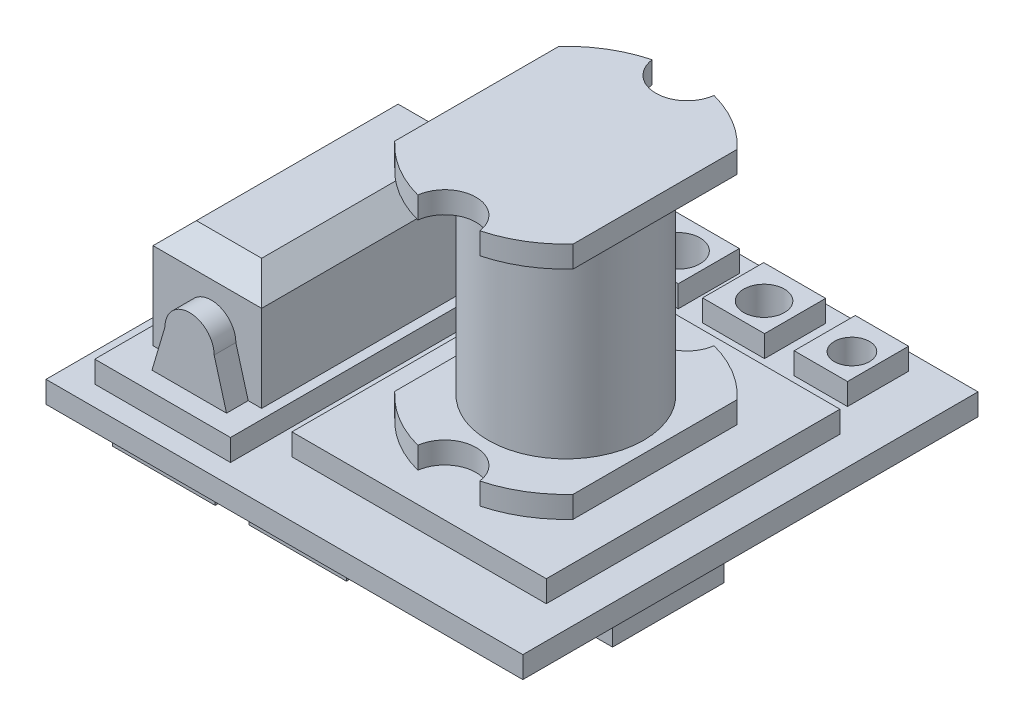
SolidWorks part; units mm, degrees
ref_plane "Front Plane" through (0, 0, 0) normal (0, 0, 1) x (1, 0, 0)
ref_plane "Top Plane" through (0, 0, 0) normal (0, 1, 0) x (1, 0, 0)
ref_plane "Right Plane" through (0, 0, 0) normal (1, 0, 0) x (0, 0, -1)
sketch "Sketch1" plane through (0, 0, 0) normal (0, 1, 0) x (1, 0, 0)
  line L1 (5.5, 5.25) -> (-5.5, 5.25)
  line L2 (5.5, 5.25) -> (5.5, -5.25)
  line L3 (5.5, -5.25) -> (-5.5, -5.25)
  line L4 (-5.5, 5.25) -> (-5.5, -5.25)
  line L5 (5.5, 5.25) -> (-5.5, -5.25) construction
  line L6 (5.5, -5.25) -> (-5.5, 5.25) construction
  point P0 (0, 0)
  dimension "D1" = 11
  dimension "D2" = 10.5
extrude "Boss-Extrude1" add sketch "Sketch1" along normal blind 7.5
sketch "Sketch2" plane through (0, 7.5, 0) normal (0, 1, 0) x (1, 0, 0)
  line L4 (-5.5, 5.25) -> (-5.5, -5.25)
  line L5 (-5.5, -5.25) -> (5.5, -5.25)
  line L6 (5.5, -5.25) -> (5.5, 5.25)
  line L7 (5.5, 5.25) -> (-5.5, 5.25)
  line L8 (-5.5, 5.25) -> (-5.5, -5.25)
  line L9 (-5.5, -5.25) -> (5.5, -5.25)
  line L10 (5.5, -5.25) -> (5.5, 5.25)
  line L11 (5.5, 5.25) -> (-5.5, 5.25)
  circle A0 centre (1.8204, -0.5759) radius 2.7953
  point P2 (2.0348, -1.6391)
  point P5 (1.5119, -1.2576)
  point P8 (1.8204, -0.5759)
  dimension "D1" = 0
extrude "Cut-Extrude1" cut sketch "Sketch2" against normal blind 6
sketch "Sketch4" plane through (0, 7.5, 0) normal (0, 1, 0) x (1, 0, 0)
  line L2 (3.8774, 1.3168) -> (3.8774, -2.4687)
  line L4 (-0.2365, 1.3168) -> (-0.2365, -2.4687)
  arc A0 (3.8774, -2.4687) -> (3.8774, 1.3168) centre (1.8204, -0.5759) ccw
  circle A1 centre (1.8204, -0.5759) radius 2.7953
  arc A2 (-0.2365, 1.3168) -> (-0.2365, -2.4687) centre (1.8204, -0.5759) ccw
  dimension "D1" = 0
extrude "Cut-Extrude2" cut sketch "Sketch4" against normal blind 6
sketch "Sketch5" plane through (0, 1.5, 0) normal (0, 1, 0) x (1, 0, 0)
  line L1 (-1.1135, -3.9629) -> (4.7543, -3.9629)
  line L2 (-1.1135, -3.9629) -> (-1.1135, 2.811)
  line L3 (-1.1135, 2.811) -> (4.7543, 2.811)
  line L4 (4.7543, -3.9629) -> (4.7543, 2.811)
  line L5 (-1.1135, -3.9629) -> (4.7543, 2.811) construction
  line L6 (-1.1135, 2.811) -> (4.7543, -3.9629) construction
  line L7 (-4.8411, 2.811) -> (-1.71, 2.811)
  line L8 (-4.8411, 2.811) -> (-4.8411, -4.7841)
  line L9 (-4.8411, -4.7841) -> (-1.71, -4.7841)
  line L10 (-1.71, 2.811) -> (-1.71, -4.7841)
  line L11 (-3.2755, 4.8605) -> (-1.71, 4.8605)
  line L12 (-3.2755, 4.8605) -> (-3.2755, 3.4503)
  line L13 (-3.2755, 3.4503) -> (-1.71, 3.4503)
  line L14 (-1.71, 4.8605) -> (-1.71, 3.4503)
  line L15 (-1.1135, 4.8605) -> (0.3838, 4.8605)
  line L16 (-1.1135, 4.8605) -> (-1.1135, 3.4503)
  line L17 (-1.1135, 3.4503) -> (0.3838, 3.4503)
  line L18 (0.3838, 4.8605) -> (0.3838, 3.4503)
  line L19 (0.946, 4.8605) -> (2.3753, 4.8605)
  line L20 (0.946, 4.8605) -> (0.946, 3.4503)
  line L21 (0.946, 3.4503) -> (2.3753, 3.4503)
  line L22 (2.3753, 4.8605) -> (2.3753, 3.4503)
  line L23 (3.0591, 4.8605) -> (4.2884, 4.8605)
  line L24 (3.0591, 4.8605) -> (3.0591, 3.4503)
  line L25 (3.0591, 3.4503) -> (4.2884, 3.4503)
  line L26 (4.2884, 4.8605) -> (4.2884, 3.4503)
  point P0 (1.8204, -0.5759)
extrude "Boss-Extrude2" add sketch "Sketch5" along normal blind 0.5
sketch "Sketch6" plane through (0, 7.5, 0) normal (0, 1, 0) x (1, 0, 0)
  line L0 (3.8774, -0.5759) -> (-0.2365, -0.5759) construction
  line L1 (3.8774, 1.3168) -> (3.8774, -2.4687) construction
  line L2 (-0.2365, -2.4687) -> (-0.2365, 1.3168) construction
  circle A0 centre (1.8204, 2.2193) radius 0.7202
  arc A1 (3.8774, 1.3168) -> (-0.2365, 1.3168) centre (1.8204, -0.5759) ccw construction
  circle A2 centre (1.8204, -3.3712) radius 0.7202
extrude "Cut-Extrude3" cut sketch "Sketch6" against normal up to surface (5.5 mm away) up to face at (1.8204, 2, 0.5759)
sketch "Sketch7" plane through (0, 7.5, 0) normal (0, 1, 0) x (1, 0, 0)
  line L1 (-0.5929, 2.9683) -> (5.723, 2.9683)
  line L2 (-0.5929, 2.9683) -> (-0.5929, -4.3455)
  line L3 (-0.5929, -4.3455) -> (5.723, -4.3455)
  line L4 (5.723, 2.9683) -> (5.723, -4.3455)
  circle A0 centre (1.8204, -0.5759) radius 1.7928
extrude "Cut-Extrude4" cut sketch "Sketch7" against normal blind 4.5 from offset 0.5 offset against normal yes
sketch "Sketch8" plane through (0, 2, 0) normal (0, 1, 0) x (1, 0, 0)
  line L1 (-4.4357, -3.8447) -> (-1.931, -3.8447)
  line L2 (-4.4357, -3.8447) -> (-4.4357, 1.8095)
  line L3 (-4.4357, 1.8095) -> (-1.931, 1.8095)
  line L4 (-1.931, -3.8447) -> (-1.931, 1.8095)
extrude "Boss-Extrude3" add sketch "Sketch8" along normal blind 2.5
chamfer "Chamfer1" distance 0.5 angle 45 4 edges at (-1.931, 4.5, 1.0176) (-3.1833, 4.5, -1.8095) (-4.4357, 4.5, 1.0176) (-3.1833, 4.5, 3.8447)
sketch "Sketch9" plane through (0, 0, 3.8447) normal (0, 0, 1) x (1, 0, 0)
  line L0 (-3.6594, 3.0182) -> (-3.9604, 2)
  line L1 (-4.4357, 2) -> (-1.931, 2) construction
  line L2 (-3.9604, 2) -> (-2.2409, 2)
  line L3 (-2.2409, 2) -> (-2.5258, 3.0182)
  arc A0 (-2.5258, 3.0182) -> (-3.6594, 3.0182) centre (-3.0926, 3.0182) ccw
extrude "Boss-Extrude4" add sketch "Sketch9" against normal blind 6 and the other way blind 0.5
ref_plane "Plane1" through (-3.2755, 2, -4.8605) normal (0, 0, 1) x (1, 0, 0)
sketch "Sketch11" plane through (0, 2, 0) normal (0, 1, 0) x (1, 0, 0)
  circle A0 centre (-2.4343, 4.1009) radius 0.4483
  circle A1 centre (-0.2821, 4.1009) radius 0.5192
  circle A2 centre (1.7143, 4.1009) radius 0.47
  circle A3 centre (3.7404, 4.1009) radius 0.4053
extrude "Cut-Extrude5" cut sketch "Sketch11" against normal blind 6
sketch "Sketch12" plane through (0, 0, 0) normal (0, -1, 0) x (1, 0, 0)
  line L1 (8.6056, -13.8889) -> (-7.3807, -13.8889)
  line L2 (8.6056, -13.8889) -> (8.6056, 8.3323)
  line L3 (8.6056, 8.3323) -> (-7.3807, 8.3323)
  line L4 (-7.3807, -13.8889) -> (-7.3807, 8.3323)
extrude "Cut-Extrude6" cut sketch "Sketch12" against normal blind 1
ref_plane "Plane2" through (5.5, 1, 5.25) normal (0, 0, 1) x (1, 0, 0)
sketch "Sketch14" plane through (0, 1, 0) normal (0, -1, 0) x (1, 0, 0)
  line L1 (-4.8973, 4.3188) -> (-2.5301, 4.3188)
  line L2 (-4.8973, 4.3188) -> (-4.8973, -1.0039)
  line L3 (-4.8973, -1.0039) -> (-2.5301, -1.0039)
  line L4 (-2.5301, 4.3188) -> (-2.5301, -1.0039)
  line L5 (-1.7533, 4.3188) -> (0.4997, 4.3188)
  line L6 (-1.7533, 4.3188) -> (-1.7533, -1.0039)
  line L7 (-1.7533, -1.0039) -> (0.4997, -1.0039)
  line L8 (0.4997, 4.3188) -> (0.4997, -1.0039)
  line L9 (1.0111, 2.5661) -> (4.8852, 2.5661)
  line L10 (1.0111, 2.5661) -> (1.0111, 0)
  line L11 (1.0111, 0) -> (4.8852, 0)
  line L12 (4.8852, 2.5661) -> (4.8852, 0)
extrude "Boss-Extrude5" add sketch "Sketch14" along normal blind 1
sketch "Sketch15" plane through (0, 1, 0) normal (0, -1, 0) x (1, 0, 0)
  line L1 (1.6149, -0.9607) -> (1.9106, -0.9607)
  line L2 (1.6149, -0.9607) -> (1.6149, 0.3165)
  line L3 (1.6149, 0.3165) -> (1.9106, 0.3165)
  line L4 (1.9106, -0.9607) -> (1.9106, 0.3165)
  line L5 (2.733, -0.9607) -> (3.0287, -0.9607)
  line L6 (2.733, -0.9607) -> (2.733, 0.3165)
  line L7 (2.733, 0.3165) -> (3.0287, 0.3165)
  line L8 (3.0287, -0.9607) -> (3.0287, 0.3165)
  line L9 (3.914, -0.9607) -> (4.2097, -0.9607)
  line L10 (3.914, -0.9607) -> (3.914, 0.3165)
  line L11 (3.914, 0.3165) -> (4.2097, 0.3165)
  line L12 (4.2097, -0.9607) -> (4.2097, 0.3165)
  line L13 (1.7627, 2.2426) -> (4.0619, 2.2426)
  line L14 (1.7627, 2.2426) -> (1.7627, 3.8324)
  line L15 (1.7627, 3.8324) -> (4.0619, 3.8324)
  line L16 (4.0619, 2.2426) -> (4.0619, 3.8324)
extrude "Boss-Extrude6" add sketch "Sketch15" along normal blind 0.25
